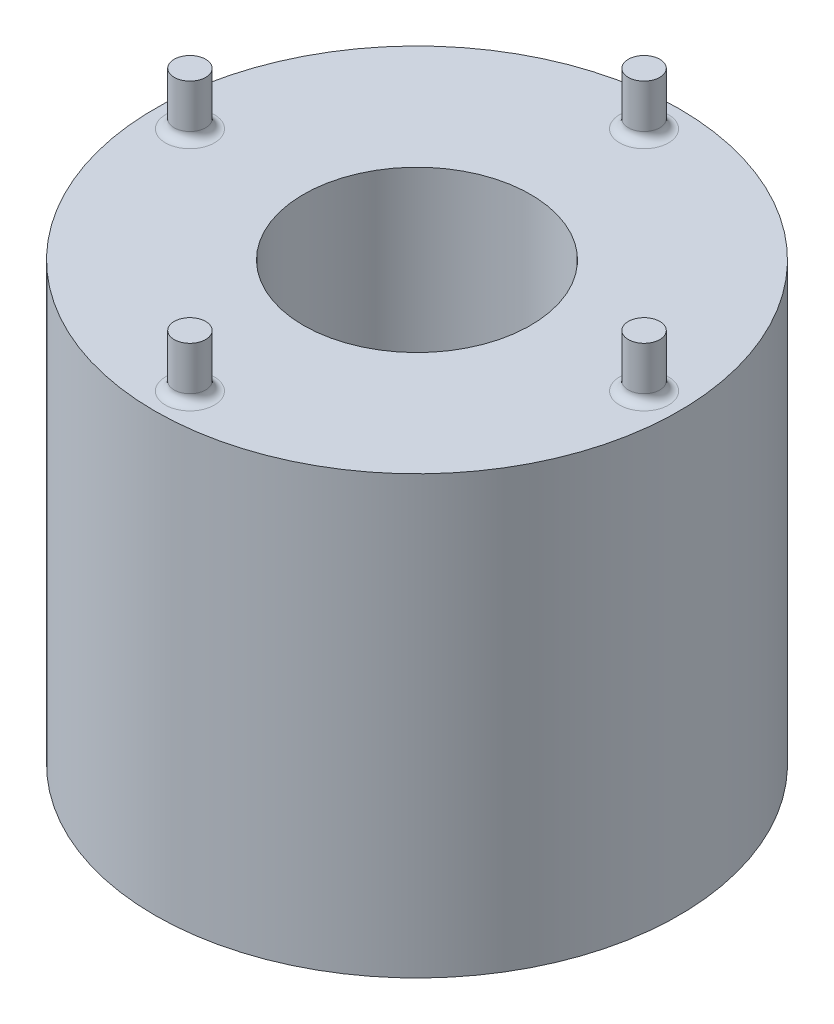
SolidWorks part; units mm, degrees
ref_plane "Front Plane" through (0, 0, 0) normal (0, 0, 1) x (1, 0, 0)
ref_plane "Top Plane" through (0, 0, 0) normal (0, 1, 0) x (1, 0, 0)
ref_plane "Right Plane" through (0, 0, 0) normal (1, 0, 0) x (0, 0, -1)
sketch "Sketch1" plane through (0, 0, 0) normal (0, 1, 0) x (1, 0, 0)
  circle A1 centre (0, 0) radius 15
  dimension "D2" = 30
extrude "Boss-Extrude1" add sketch "Sketch1" along normal blind 10 contours A1
sketch "Sketch2" plane through (0, 10, 0) normal (0, 1, 0) x (1, 0, 0)
  circle A0 centre (0, 0) radius 15
  circle A2 centre (0, 0) radius 15 construction
extrude "Boss-Extrude2" add sketch "Sketch2" along normal blind 15
sketch "Sketch3" plane through (0, 25, 0) normal (0, 1, 0) x (1, 0, 0)
  line L0 (0, -5.5) -> (0, 5.5) construction
  line L1 (-5.5, 0) -> (5.5, 0) construction
  circle A0 centre (0, -13) radius 0.9
  dimension "D1" = 1.8
  dimension "D2" = 13
extrude "Boss-Extrude3" add sketch "Sketch3" along normal blind 3
fillet "Fillet1" radius 0.5 1 edges at (0, 25, 13.9)
pattern_circular "CirPattern1" count 4 every 90 about axis through (0, 0, 0) along (0, 1, 0) of "Boss-Extrude3", "Fillet1"
sketch "Sketch5" plane through (0, 25, 0) normal (0, 1, 0) x (1, 0, 0)
  circle A0 centre (0, 0) radius 6.5
  dimension "D1" = 13
extrude "Cut-Extrude1" cut sketch "Sketch5" against normal blind 10
sketch "Sketch6" plane through (0, 15, 0) normal (0, 1, 0) x (1, 0, 0)
  circle A0 centre (0, 0) radius 1.75
  dimension "D1" = 3.5
extrude "Cut-Extrude2" cut sketch "Sketch6" against normal blind 10
